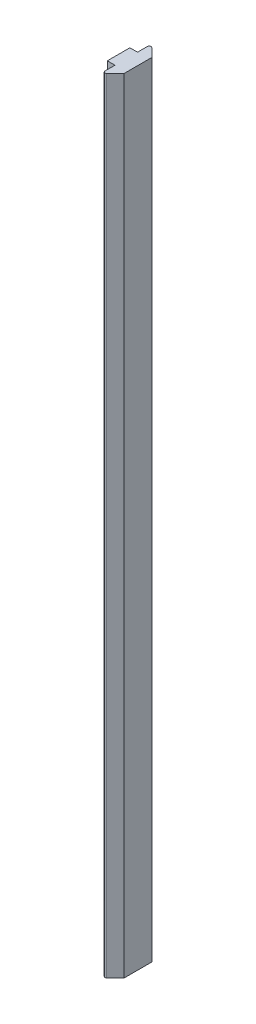
SolidWorks part; units mm, degrees
ref_plane "Front Plane" through (0, 0, 0) normal (0, 0, 1) x (1, 0, 0)
ref_plane "Top Plane" through (0, 0, 0) normal (0, 1, 0) x (1, 0, 0)
ref_plane "Right Plane" through (0, 0, 0) normal (1, 0, 0) x (0, 0, -1)
sketch "Sketch1" plane through (0, 0, 0) normal (0, 1, 0) x (1, 0, 0)
  line L0 (-4.6893, 3.1281) -> (-4.6893, 3.6281) construction
  line L1 (-4.6893, 3.6281) -> (-5.1893, 3.6281) construction
  line L2 (-4.7927, -3.1458) -> (-4.7927, -3.1281) construction
  line L3 (-5.1893, -3.1458) -> (-4.7927, -3.1458) construction
  line L6 (-4.7927, -3.1281) -> (-3.4893, -3.1281) construction
  line L7 (-3.4893, 3.1281) -> (-4.6893, 3.1281) construction
  line L8 (-2.2944, -5.9224) -> (0, -3.6281) construction
  line L9 (-3.4893, -3.1281) -> (-3.4893, -5.4274) construction
  line L10 (-3.4893, 5.4274) -> (-3.4893, 3.1281) construction
  line L11 (0, 3.6281) -> (-2.2944, 5.9224) construction
  line L12 (0, 3.6281) -> (0, -3.6281) construction
  line L14 (-3.2393, -2.8781) -> (-3.2393, -5.4274)
  line L15 (-2.4711, -5.7456) -> (-0.25, -3.5245)
  line L16 (-0.25, 3.5245) -> (-0.25, -3.5245)
  line L17 (-0.25, 3.5245) -> (-2.4711, 5.7456)
  line L18 (-3.2393, 5.4274) -> (-3.2393, 2.8781)
  line L19 (-3.2393, 2.8781) -> (-4.9393, 2.8781)
  line L22 (-5.1893, 2.8781) -> (-5.1893, -2.8781)
  line L23 (-3.2393, -2.8781) -> (-5.1893, -2.8781)
  line L24 (-5.1893, -2.8958) -> (-5.0427, -2.8958) construction
  line L25 (-5.0427, -2.8958) -> (-5.0427, -2.8781) construction
  line L26 (-5.0427, -2.8781) -> (-3.2393, -2.8781) construction
  line L27 (-4.9393, 2.8781) -> (-4.9393, 3.3781) construction
  line L28 (-4.9393, 2.8781) -> (-5.1893, 2.8781)
  line L31 (-4.9393, 3.3781) -> (-5.1893, 3.3781) construction
  arc A0 (-3.2393, -5.4274) -> (-2.4711, -5.7456) centre (-2.7893, -5.4274) ccw
  arc A1 (-2.4711, 5.7456) -> (-3.2393, 5.4274) centre (-2.7893, 5.4274) ccw
  arc A4 (-3.4893, -5.4274) -> (-2.2944, -5.9224) centre (-2.7893, -5.4274) ccw construction
  arc A5 (-2.2944, 5.9224) -> (-3.4893, 5.4274) centre (-2.7893, 5.4274) ccw construction
  point P8 (0, 0)
  dimension "D1" = 0.25
extrude "Boss-Extrude1" add sketch "Sketch1" along normal blind 200
